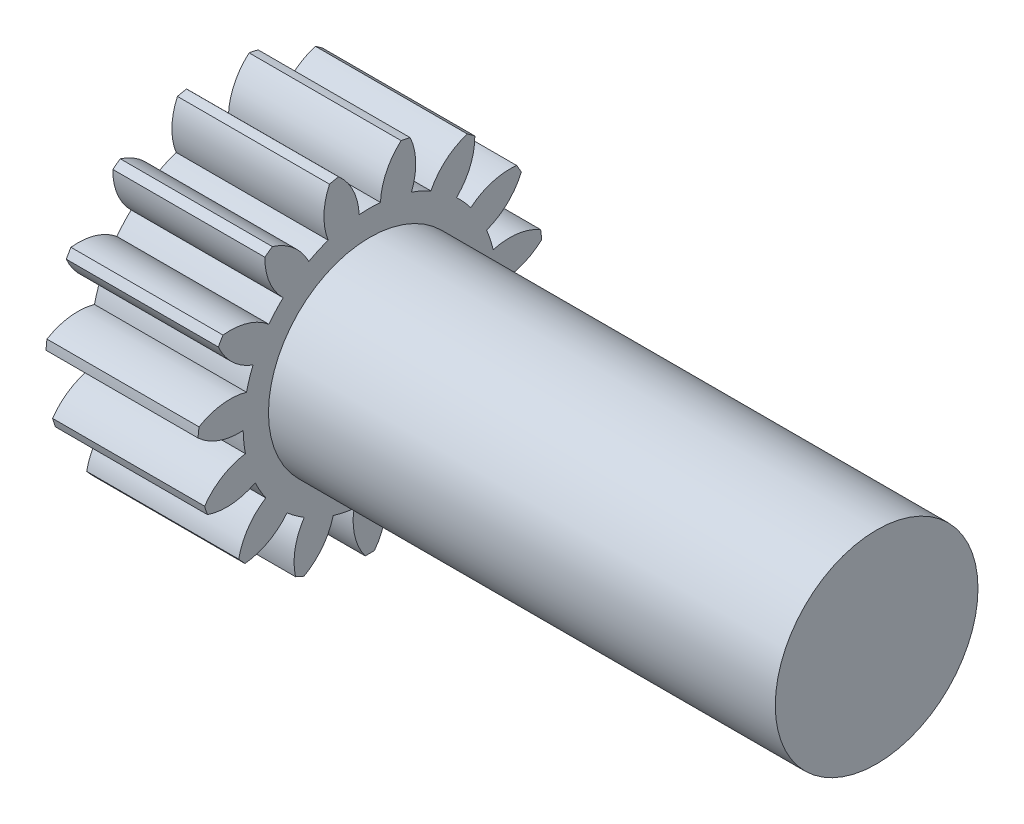
SolidWorks part; units mm, degrees
ref_plane "Plane1" through (0, 0, 0) normal (0, 0, 1) x (1, 0, 0)
ref_plane "Plane2" through (0, 0, 0) normal (0, 1, 0) x (1, 0, 0)
ref_plane "Plane3" through (0, 0, 0) normal (1, 0, 0) x (0, 0, -1)
sketch "HoldingSke" plane through (0, 0, 0) normal (0, 1, 0) x (1, 0, 0)
  line L0 (0, 0) -> (0.483, -0.1294)
  line L1 (-15, 0) -> (100, 0) construction
  line L2 (0, 0) -> (-2.1039, 2.3779)
  line L3 (0, 0) -> (-11.863, 4.5341)
  line L4 (0, 0) -> (8.3417, 2.2352)
  line L5 (0, 0) -> (-46.8476, -17.4728)
  line L6 (0, 0) -> (-12.4344, -8.3896)
  line L7 (-2.1039, 2.3779) -> (8.6586, 51.2059)
  line L8 (-76.2, 54.61) -> (-75.3, 54.61)
  line L9 (-71.009, 38.7566) -> (-53.1078, 45.2721)
  line L10 (-76.2, 71.12) -> (104.1128, 71.12)
  line L11 (0, 0) -> (-15, 0)
  line L12 (-76.2, 101.6) -> (-76.133, 101.6)
  line L13 (24.9733, 27.94) -> (52.9518, 28.4284)
  line L14 (24.9733, 27.94) -> (24.9743, 27.94)
  line L15 (24.9733, 27.94) -> (100.4006, 29.5858)
  line L16 (-63.627, -2) -> (-12.827, -2)
  circle A0 centre (0, 0) radius 2.5
  circle A1 centre (0, 0) radius 12.499
  circle A2 centre (0, 0) radius 37.5
  circle A3 centre (0, 0) radius 2.5
  dimension "MHD" = 24.998
  dimension "Hub_dia" = 75
  dimension "Bore" = 5
  dimension "MBD" = 5
  dimension "Num_teeth" = 15
  dimension "Pitch" = 0.5
  dimension "Overall_len" = 50
  dimension "Show_teeth" = 15
  dimension "Thickness" = 15
  dimension "OAL" = 50.0001
  dimension "T_dim" = 0.9
  dimension "Ap" = 20
  dimension "H" = 19.05
  dimension "Pitch_radius" = 180.3128
  dimension "Width" = 15
  dimension "Backlash" = 0.067
  dimension "Addendum_fac" = 1
  dimension "Dedendum_fac" = 1.25
  dimension "Clearance_fac" = 0.25
  dimension "Dedendum_add" = 0.001
  dimension "Module" = 2
sketch "BasProSke" plane through (0, 0, 0) normal (0, 1, 0) x (1, 0, 0)
  line L0 (-10, 0) -> (60, 0) construction
  line L1 (0, 0) -> (0, 17)
  line L2 (0, 0) -> (15, 0)
  line L3 (15, 0) -> (15, 17)
  line L4 (15, 17) -> (0, 17)
  dimension "Thickness" = 15
  dimension "Diameter" = 34
revolve "Base-Revolve" add sketch "BasProSke" angle 360 about L0
sketch "TooCutSke" plane through (0, 0, 0) normal (1, 0, 0) x (0, 0, -1)
  line L1 (0, 0) -> (0, 107) construction
  line L2 (0, 0) -> (-1.6851, 14.905) construction
  line L3 (0, 0) -> (-6.2081, 29.2069) construction
  line L4 (-1.6851, 14.905) -> (-3.1041, 14.6034) construction
  arc A0 (1.0501, 12.4548) -> (-1.0501, 12.4548) centre (0, 0) ccw
  arc A1 (3.1109, 16.7388) -> (-3.1109, 16.7388) centre (0, 0) ccw
  circle A2 centre (0, 0) radius 15 construction
  circle A3 centre (0, 0) radius 14.0954 construction
  arc A4 (-1.0501, 12.4548) -> (-3.1109, 16.7388) centre (-7.045, 12.2085) ccw
  arc A5 (3.1109, 16.7388) -> (1.0501, 12.4548) centre (7.045, 12.2085) ccw
  dimension "Root_dia" = 24.998
  dimension "Overcut_dia" = 34.0508
  dimension "Pitch_dia" = 30
  dimension "Base_dia" = 28.1908
  dimension "Flank_rad" = 6
  dimension "Half_ang" = 12
  dimension "Half_CT" = 1.4507
extrude "ToothCut" cut sketch "TooCutSke" along normal through all
fillet "Breaks" [suppressed] radius 0.04
fillet "RootFillets" [suppressed] radius 0.501
pattern_circular "TeethCuts" count 15 every 24 about axis through (-10, 0, 0) along (1, 0, 0) of "ToothCut", "RootFillets", "Breaks"
sketch "HubNeaOneSke" plane through (0, 0, 0) normal (-1, 0, 0) x (0, 0, 1)
  circle A0 centre (0, 0) radius 12.499
  dimension "Diameter" = 24.998
extrude "HubNearOne" [suppressed] add sketch "HubNeaOneSke" along normal blind 35.0001
sketch "HubNeaBotSke" plane through (0, 0, 0) normal (-1, 0, 0) x (0, 0, 1)
  circle A0 centre (0, 0) radius 12.499
  dimension "Diameter" = 24.998
extrude "HubNearBoth" [suppressed] add sketch "HubNeaBotSke" along normal blind 17.5
ref_plane "FarPln" through (15, 0, 0) normal (1, 0, 0) x (0, 0, -1)
sketch "HubFarSke" plane through (15, 0, 0) normal (1, 0, 0) x (0, 0, -1)
  circle A0 centre (0, 0) radius 12.499
  dimension "Diameter" = 24.998
extrude "HubFar" [suppressed] add sketch "HubFarSke" along normal blind 17.5
sketch "BorSke" plane through (0, 0, 0) normal (1, 0, 0) x (0, 0, -1)
  circle A0 centre (0, 0) radius 2.5
  dimension "Diameter" = 5
extrude "Bore" cut sketch "BorSke" along normal mid plane 100.0001
sketch "KeySke" plane through (0, 0, 0) normal (1, 0, 0) x (0, 0, -1)
  line L0 (-1, 0) -> (-1, 3.4)
  line L1 (-1, 3.4) -> (1, 3.4)
  line L2 (1, 3.4) -> (1, 0)
  line L3 (0, 0) -> (0, 34) construction
  line L4 (-1, 0) -> (1, 0)
  dimension "Offset" = 3.4
  dimension "Width" = 2
extrude "Keyway" [suppressed] cut sketch "KeySke" along normal mid plane 100.0001
pattern_circular "Keyway2" [suppressed] count 2 every 90 about axis through (-10, 0, 0) along (1, 0, 0)
sketch "Sketch1" plane through (15, 0, 0) normal (1, 0, 0) x (0, 0, -1)
  circle A0 centre (0, 0) radius 10
  dimension "D1" = 20
extrude "Boss-Extrude1" add sketch "Sketch1" along normal blind 50
sketch "Sketch2" plane through (0, 0, 0) normal (-1, 0, 0) x (0, 0, 1)
  circle A0 centre (0, 0) radius 2.5
extrude "Cut-Extrude3" cut sketch "Sketch2" against normal blind 20
equation "' \"Module@HoldingSke\" = 6.35"
equation "' \"Num_teeth@HoldingSke\" = 12"
equation "' \"Ap@HoldingSke\" =  20"
equation "' \"Ap@HoldingSke\" = 20"
equation "' \"Width@HoldingSke\" = 0.5 * 25.4"
equation "' \"Hub_dia@HoldingSke\"= 1 * 25.4"
equation "' \"Hub_dia@HoldingSke\" = 1 * 25.4"
equation "' \"Overall_len@HoldingSke\" = 1.0 * 25.4"
equation "' \"Bore@HoldingSke\" = 0.75 * 25.4"
equation "' \"T_dim@HoldingSke\" = 0.1 * 25.4"
equation "' \"Width@KeySke\" = 0.25 * 25.4"
equation "' \"Show_teeth@HoldingSke\" = 13"
equation "' \"Backlash@HoldingSke\" = 0.009 * 25.4"
equation "' \"Addendum_fac@HoldingSke\" = 1.0"
equation "' \"Dedendum_fac@HoldingSke\" = 1.25"
equation "' \"Dedendum_add@HoldingSke\" = 0.00005 * 25.4"
equation "' \"Clearance_fac@HoldingSke\" = 0.25"
equation "\"Pitch@HoldingSke\" = 1 / \"Module@HoldingSke\""
equation "\"Overcut_dia@TooCutSke\" = (\"Num_teeth@HoldingSke\" + 2 * \"Addendum_fac@HoldingSke\") / \"Pitch@HoldingSke\" + 0.002 * 25.4"
equation "\"Pitch_dia@TooCutSke\" = \"Num_teeth@HoldingSke\" / \"Pitch@HoldingSke\""
equation "\"Base_dia@TooCutSke\" = \"Num_teeth@HoldingSke\" / \"Pitch@HoldingSke\" * cos((\"Ap@HoldingSke\"  * 3.14159265 / 180))"
equation "\"Root_dia@TooCutSke\" = (\"Num_teeth@HoldingSke\" + 2) / \"Pitch@HoldingSke\" - 2 * (\"Addendum_fac@HoldingSke\" + \"Dedendum_fac@HoldingSke\") / \"Pitch@HoldingSke\" - \"Dedendum_add@HoldingSke\" * 2"
equation "\"Half_ang@TooCutSke\" = 180 / \"Num_teeth@HoldingSke\""
equation "\"Half_CT@TooCutSke\" = \"Num_teeth@HoldingSke\" / \"Pitch@HoldingSke\" * sin((3.14159265 / 2 / \"Num_teeth@HoldingSke\")) / 2 - 7 * \"Backlash@HoldingSke\" / 4"
equation "\"Flank_rad@TooCutSke\" = \"Num_teeth@HoldingSke\" / \"Pitch@HoldingSke\" / 5"
equation "\"Radius@RootFillets\" = \"Clearance_fac@HoldingSke\" / \"Pitch@HoldingSke\" + \"Dedendum_add@HoldingSke\""
equation "\"Break_rad@Breaks\" = 0.02 / \"Pitch@HoldingSke\""
equation "\"Thickness@HoldingSke\" = \"Width@HoldingSke\""
equation "\"OAL@HoldingSke\" = \"Thickness@HoldingSke\""
equation "\"MHD@HoldingSke\" = (\"Num_teeth@HoldingSke\" + 2) / \"Pitch@HoldingSke\" - 2 * (\"Addendum_fac@HoldingSke\" + \"Dedendum_fac@HoldingSke\")  / \"Pitch@HoldingSke\" - \"Dedendum_add@HoldingSke\" * 2"
equation "\"MBD@HoldingSke\" = (\"Num_teeth@HoldingSke\" + 2) / \"Pitch@HoldingSke\" - 2 * (\"Addendum_fac@HoldingSke\" + \"Dedendum_fac@HoldingSke\")  / \"Pitch@HoldingSke\" - \"Dedendum_add@HoldingSke\" * 2 - 0.002 * 25.4"
equation "\"MHD@HoldingSke\" = ((sgn( \"MHD@HoldingSke\" - \"Hub_dia@HoldingSke\" )-1)*( \"MHD@HoldingSke\" - \"Hub_dia@HoldingSke\" ))/-2+ \"Hub_dia@HoldingSke\""
equation "\"MBD@HoldingSke\" = ((sgn( \"MBD@HoldingSke\" - \"Bore@HoldingSke\" )-1)*( \"MBD@HoldingSke\" - \"Bore@HoldingSke\" ))/-2+ \"Bore@HoldingSke\""
equation "\"OAL@HoldingSke\" = ((sgn( \"OAL@HoldingSke\" - \"Overall_len@HoldingSke\" )+1)*( \"OAL@HoldingSke\" - \"Overall_len@HoldingSke\" ))/2 + \"Overall_len@HoldingSke\" + 0.000002 * 25.4"
equation "\"Num_teeth@TeethCuts\" = int( \"Show_teeth@HoldingSke\" ) + 1"
equation "\"Num_teeth@TeethCuts\" = ((sgn( \"Num_teeth@TeethCuts\" - \"Num_teeth@HoldingSke\" )-1)*( \"Num_teeth@TeethCuts\" - \"Num_teeth@HoldingSke\" ))/-2+ \"Num_teeth@HoldingSke\""
equation "\"Num_teeth@TeethCuts\" = ((sgn( \"Num_teeth@TeethCuts\" - 2.0)+1)*( \"Num_teeth@TeethCuts\" - 2.0))/2 +2.0"
equation "\"Angle@TeethCuts\" = 360.0 / \"Num_teeth@HoldingSke\""
equation "\"Diameter@BasProSke\" = (\"Num_teeth@HoldingSke\" + 2 * \"Addendum_fac@HoldingSke\") / \"Pitch@HoldingSke\""
equation "\"Thickness@BasProSke\"  = \"Thickness@HoldingSke\""
equation "' \"Fillet_rad@BasProSke\" =  \"Thickness@HoldingSke\" * 0.05"
equation "' \"Fillet_rad@BasProSke\" = \"Thickness@HoldingSke\" * 0.05"
equation "\"MHD@HoldingSke\" = ((sgn( \"MHD@HoldingSke\" - \"Root_dia@TooCutSke\" )-1)*( \"MHD@HoldingSke\" - \"Root_dia@TooCutSke\" ))/-2+ \"Root_dia@TooCutSke\""
equation "\"Diameter@HubNeaOneSke\" = \"MHD@HoldingSke\""
equation "\"Length@HubNearOne\" = \"OAL@HoldingSke\" - \"Thickness@BasProSke\""
equation "\"Diameter@HubNeaBotSke\" = \"MHD@HoldingSke\""
equation "\"Length@HubNearBoth\" = ( \"OAL@HoldingSke\" - \"Thickness@BasProSke\" ) / 2.0"
equation "\"Thickness@FarPln\" = \"Thickness@BasProSke\""
equation "\"Diameter@HubFarSke\" = \"MHD@HoldingSke\""
equation "\"Length@HubFar\" = ( \"OAL@HoldingSke\" - \"Thickness@BasProSke\" ) / 2.0"
equation "\"Diameter@BorSke\" = \"MBD@HoldingSke\""
equation "\"D1@Bore\" = \"OAL@HoldingSke\" * 2.0"
equation "\"D1@Keyway\" = \"OAL@HoldingSke\" * 2.0"
equation "\"Offset@KeySke\" = \"T_dim@HoldingSke\" + \"MBD@HoldingSke\" / 2.0"
